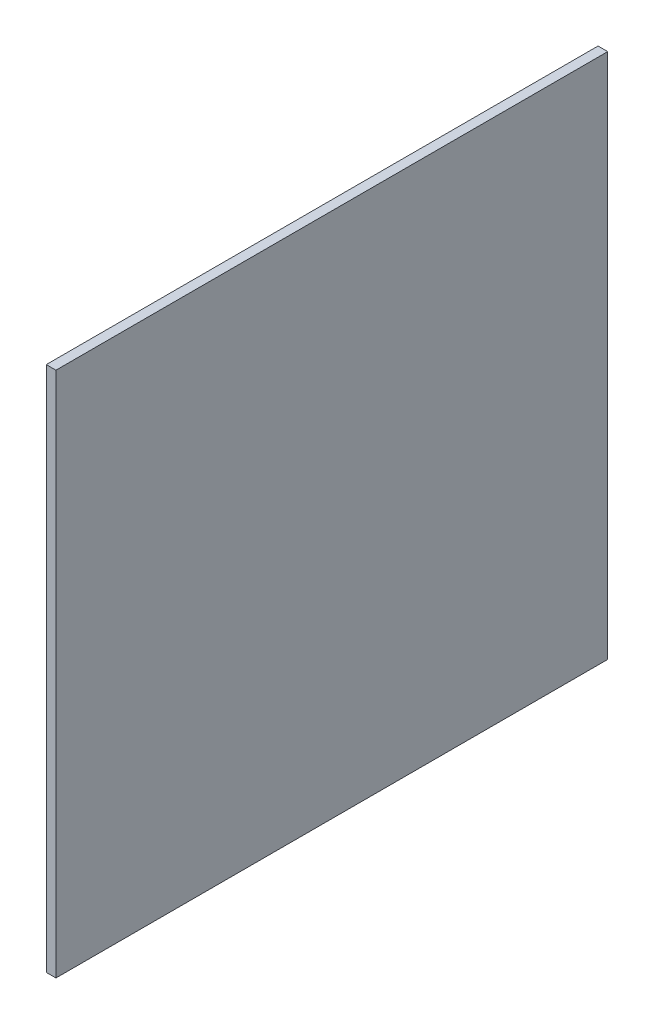
SolidWorks part; units mm, degrees
material "未指定"
ref_plane "正面" through (0, 0, 0) normal (0, 0, 1) x (1, 0, 0)
ref_plane "平面" through (0, 0, 0) normal (0, 1, 0) x (1, 0, 0)
ref_plane "右側面" through (0, 0, 0) normal (1, 0, 0) x (0, 0, -1)
sketch "ｽｹｯﾁ1" plane through (0, 0, 0) normal (1, 0, 0) x (0, 0, -1)
  line L0 (45.6, 0) -> (-45.6, 0)
  line L1 (-45.6, 0) -> (-45.6, 87)
  line L2 (-45.6, 87) -> (45.6, 87)
  line L3 (45.6, 87) -> (45.6, 0)
  line L4 (0, 0) -> (0, 25) construction
  dimension "D1" = 91.2
  dimension "D2" = 87
extrude "基板" add sketch "ｽｹｯﾁ1" along normal mid plane 1.6
equation "\"CARD_W\" = 91.2"
equation "\"D1@ｽｹｯﾁ1\" = \"CARD_W\""
equation "\"CARD_H\" = 87"
equation "\"D2@ｽｹｯﾁ1\" = \"CARD_H\""
equation "\"PCB_T\" = 1.6"
equation "\"D1@基板\" = \"PCB_T\""
